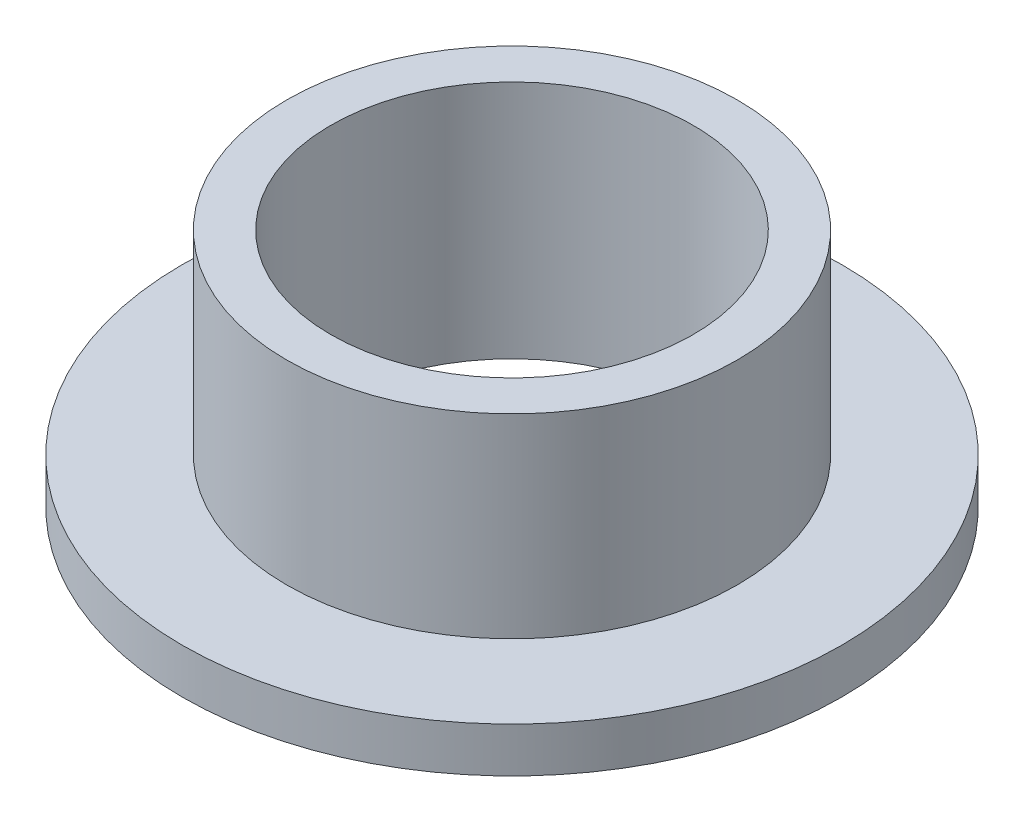
SolidWorks part; units mm, degrees
material "Polyetheretherketone (PEEK)"
ref_plane "Front" through (0, 0, 0) normal (0, 0, 1) x (1, 0, 0)
ref_plane "Top" through (0, 0, 0) normal (0, 1, 0) x (1, 0, 0)
ref_plane "Right" through (0, 0, 0) normal (1, 0, 0) x (0, 0, -1)
sketch "Sketch1" plane through (0, 0, 0) normal (0, 1, 0) x (1, 0, 0)
  circle A0 centre (0, 0) radius 4.8006
  circle A1 centre (0, 0) radius 5.9665
  circle A2 centre (0, 0) radius 8.7312
  dimension "ID" = 9.6012
  dimension "OD" = 11.9329
  dimension "FlangeOD" = 17.4625
sketch "Sketch2" plane through (0, 0, 0) normal (0, 1, 0) x (1, 0, 0)
  circle A0 centre (0, 0) radius 4.8006 construction
  circle A1 centre (0, 0) radius 5.9665 construction
  circle A2 centre (0, 0) radius 4.8006
  circle A3 centre (0, 0) radius 5.9665
extrude "Boss-Extrude1" add sketch "Sketch2" along normal blind 6.35
sketch "Sketch3" plane through (0, 0, 0) normal (0, 1, 0) x (1, 0, 0)
  circle A0 centre (0, 0) radius 8.7312 construction
  circle A1 centre (0, 0) radius 5.9665 construction
  circle A2 centre (0, 0) radius 8.7312
  circle A3 centre (0, 0) radius 5.9665
extrude "Boss-Extrude2" add sketch "Sketch3" along normal blind 1.1906
